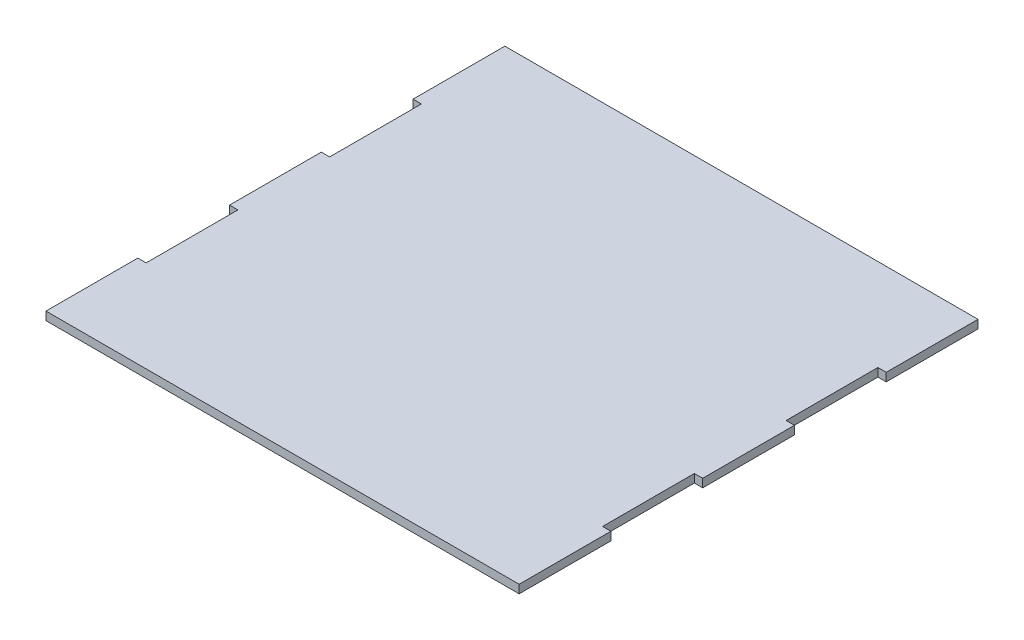
SolidWorks part; units mm, degrees
ref_plane "Ön Düzlem" through (0, 0, 0) normal (0, 0, 1) x (1, 0, 0)
ref_plane "Üst Düzlem" through (0, 0, 0) normal (0, 1, 0) x (1, 0, 0)
ref_plane "Sağ Düzlem" through (0, 0, 0) normal (1, 0, 0) x (0, 0, -1)
sketch "Sketch1" plane through (0, 0, 0) normal (0, 1, 0) x (1, 0, 0)
  line L1 (76.7, -74.385) -> (-76.7, -74.385)
  line L2 (76.7, -74.385) -> (76.7, -44.631)
  line L3 (76.7, 74.385) -> (-76.7, 74.385)
  line L4 (-76.7, -74.385) -> (-76.7, -44.631)
  line L5 (74, -14.877) -> (74, -44.631)
  line L6 (-74, 44.631) -> (-74, 14.877)
  line L7 (-76.7, -14.877) -> (-76.7, 14.877)
  line L9 (-76.7, 44.631) -> (-76.7, 74.385)
  line L11 (-74, -14.877) -> (-74, -44.631)
  line L12 (-76.7, -44.631) -> (-74, -44.631)
  line L13 (-76.7, -14.877) -> (-74, -14.877)
  line L14 (-76.7, 14.877) -> (-74, 14.877)
  line L15 (-76.7, 44.631) -> (-74, 44.631)
  line L17 (76.7, -44.631) -> (74, -44.631)
  line L18 (76.7, -14.877) -> (74, -14.877)
  line L19 (76.7, 14.877) -> (74, 14.877)
  line L20 (76.7, 44.631) -> (74, 44.631)
  line L22 (76.7, 44.631) -> (76.7, 74.385)
  line L23 (76.7, -14.877) -> (76.7, 14.877)
  line L26 (74, 44.631) -> (74, 14.877)
  point P0 (0, 0)
  dimension "D1" = 148.77
  dimension "D2" = 153.4
extrude "Boss-Extrude1" add sketch "Sketch1" along normal blind 2.7
